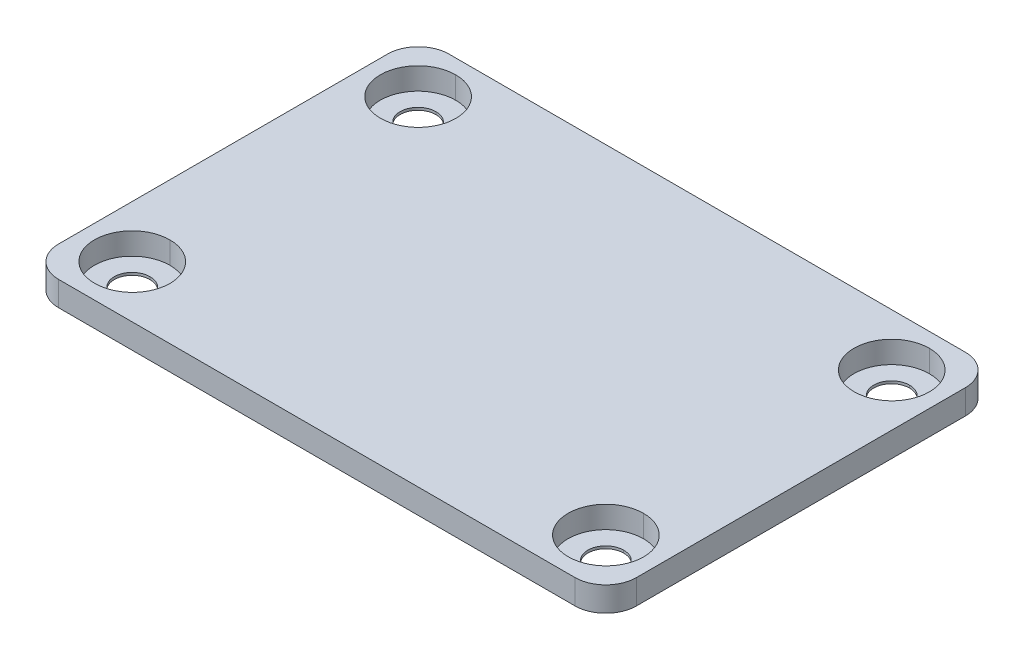
SolidWorks part; units mm, degrees
ref_plane "Front Plane" through (0, 0, 0) normal (0, 0, 1) x (1, 0, 0)
ref_plane "Top Plane" through (0, 0, 0) normal (0, 1, 0) x (1, 0, 0)
ref_plane "Right Plane" through (0, 0, 0) normal (1, 0, 0) x (0, 0, -1)
sketch "Sketch1" plane through (0, 0, 0) normal (0, 1, 0) x (1, 0, 0)
  line L1 (-34.7968, 56.2829) -> (59.2032, 56.2829)
  line L2 (-34.7968, 56.2829) -> (-34.7968, -7.2171)
  line L3 (-34.7968, -7.2171) -> (59.2032, -7.2171)
  line L4 (59.2032, 56.2829) -> (59.2032, -7.2171)
extrude "Boss-Extrude1" add sketch "Sketch1" along normal blind 4
sketch "Sketch2" plane through (0, 0, 0) normal (0, -1, 0) x (1, 0, 0)
  line L0 (-26.2968, -1.2829) -> (-26.2968, -47.7829) construction
  line L1 (-26.2968, -47.7829) -> (50.7032, -47.7829) construction
  line L2 (50.7032, -47.7829) -> (50.7032, -1.2829) construction
  line L3 (-26.2968, -1.2829) -> (50.7032, -1.2829) construction
  line L4 (-34.7968, 7.2171) -> (59.2032, 7.2171) construction
  line L5 (59.2032, -56.2829) -> (-34.7968, -56.2829) construction
  line L6 (-34.7968, -56.2829) -> (-34.7968, 7.2171) construction
  line L8 (12.2032, 7.2171) -> (12.2032, -56.2829) construction
  line L9 (0, -24.5329) -> (177.3966, -24.5329) construction
  circle A0 centre (-26.2968, -1.2829) radius 2.5
  circle A1 centre (50.7532, -1.2829) radius 2.5
  circle A4 centre (50.7532, -47.7829) radius 2.5
  circle A5 centre (-26.2968, -47.7829) radius 2.5
  circle A6 centre (50.7032, -1.2829) radius 2.5
  circle A7 centre (50.7032, -47.7829) radius 2.5
  circle A8 centre (-26.3468, -47.7829) radius 2.5
  circle A9 centre (-26.3468, -1.2829) radius 2.5
  dimension "D5" = 77.05
  dimension "D1" = 8.5
  dimension "D2" = 8.5
  dimension "D3" = 8.5
hole_wizard "CBORE SLOT for M5 Hex Head Bolt1" positions "Sketch6" profile "Sketch7" size "M5" standard "ANSI Metric" slot yes
sketch "Sketch6" plane through (0, 4, 0) normal (0, 1, 0) x (1, 0, 0)
  point P0 (-26.2968, 47.7829)
  point P3 (-26.2968, 1.2829)
  point P6 (50.7532, 47.7829)
  point P9 (50.7532, 1.2829)
  point P19 (-26.3468, 47.7829)
  point P22 (-26.3468, 1.2829)
  point P25 (50.7032, 1.2829)
  point P28 (50.7032, 47.7829)
sketch "Sketch7" plane through (-26.2968, 4, -47.7829) normal (1, 0, 0) x (0, 0, 1)
  line L0 (0, 0) -> (0, 19.7425)
  line L1 (0, 19.7425) -> (2.9, 18)
  line L2 (2.9, 18) -> (2.9, 3.58)
  line L3 (2.9, 3.58) -> (6.12, 3.58)
  line L4 (6.12, 3.58) -> (6.12, 0)
  line L5 (6.12, 0) -> (0, 0)
  line L10 (0, 19.7425) -> (-2.9, 18) construction
  line L11 (0, -6.35) -> (0, 107.95) construction
  dimension "Hole Dia." = 5.8
  dimension "Hole Depth" = 18
  dimension "C'Bore Dia." = 12.24
  dimension "C'Bore Depth" = 3.58
  dimension "Drill Angle" = 118
fillet "Fillet1" radius 5 4 edges at (59.2032, 2, 7.2171) (59.2032, 2, -56.2829) (-34.7968, 2, 7.2171) (-34.7968, 2, -56.2829)
